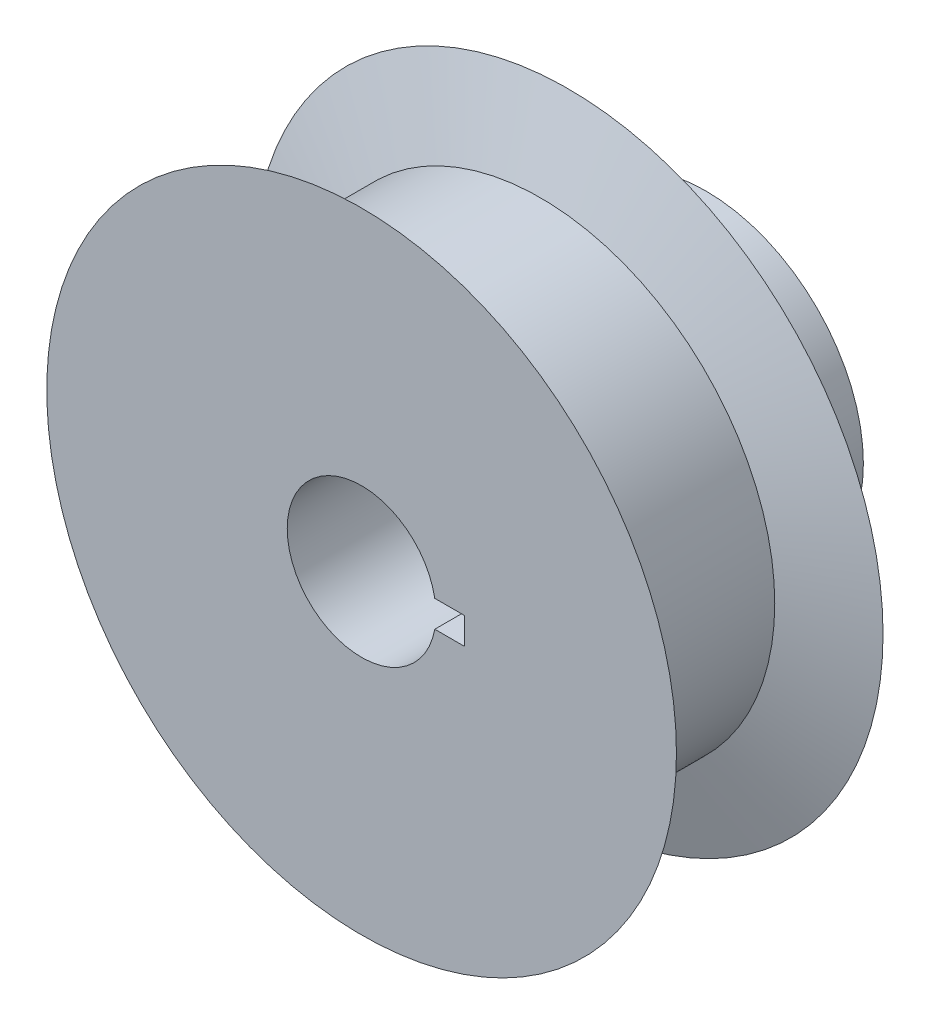
SolidWorks part; units mm, degrees
ref_plane "Front" through (0, 0, 0) normal (0, 0, 1) x (1, 0, 0)
ref_plane "Top" through (0, 0, 0) normal (0, 1, 0) x (1, 0, 0)
ref_plane "Right" through (0, 0, 0) normal (1, 0, 0) x (0, 0, -1)
sketch "Sketch1" plane through (0, 0, 0) normal (0, 0, 1) x (1, 0, 0)
  circle A0 centre (0, 0) radius 25.4
  dimension "D1" = 50.8
extrude "Boss-Extrude1" add sketch "Sketch1" along normal blind 16.6675
sketch "Sketch2" plane through (0, 0, 0) normal (0, 0, -1) x (-1, 0, 0)
  circle A0 centre (0, 0) radius 12.7
  dimension "D1" = 25.4
extrude "Boss-Extrude2" add sketch "Sketch2" along normal blind 11.1125
sketch "Sketch3" plane through (0, 0, -11.1125) normal (0, 0, -1) x (-1, 0, 0)
  line L1 (-5.9023, -1.0786) -> (-8.3153, -1.0786)
  line L3 (-5.9023, 1.0786) -> (-8.3153, 1.0786)
  line L4 (-8.3153, -1.0786) -> (-8.3153, 1.0786)
  arc A0 (-5.9023, -1.0786) -> (-5.9023, 1.0786) centre (0, 0) ccw
  dimension "D1" = 12
  dimension "D2" = 2.413
extrude "Cut-Extrude1" cut sketch "Sketch3" against normal through all
ref_plane "Plane1" through (0, -9.525, 0) normal (0, 1, 0) x (1, 0, 0)
sketch "Sketch5" plane through (0, -9.525, 0) normal (0, 1, 0) x (1, 0, 0)
  line L0 (12.7, 11.1125) -> (-12.7, 11.1125) construction
  circle A0 centre (0.5999, 5.5575) radius 3.2639
  dimension "D1" = 6.5278
  dimension "D2" = 5.555
extrude "Cut-Extrude2" cut sketch "Sketch5" against normal blind 11.1125 and the other way blind 11.1125
sketch "Sketch7" plane through (0, 0, 0) normal (1, 0, 0) x (0, 0, -1)
  line L0 (0, -25.4) -> (0, 25.4) construction
  line L1 (-16.6675, 25.4) -> (-16.6675, -25.4) construction
  line L2 (0, -25.4) -> (0, 25.4) construction
  line L3 (-16.6675, 25.4) -> (-16.6675, -25.4) construction
  line L5 (-16.6675, 25.4) -> (0, 25.4)
  line L6 (-16.6675, 0) -> (0, 0)
  line L7 (0, 25.4) -> (-2.2377, 18.9011)
  line L8 (-16.6675, 25.4) -> (-14.4297, 18.9011)
  line L9 (-14.4297, 18.9011) -> (-2.2377, 18.9011)
  point P2 (-8.3337, 18.9011)
  dimension "D1" = 38
  dimension "D2" = 12.192
  dimension "D3" = 8.3337
revolve "Cut-Revolve1" cut sketch "Sketch7" angle 360 about L6
